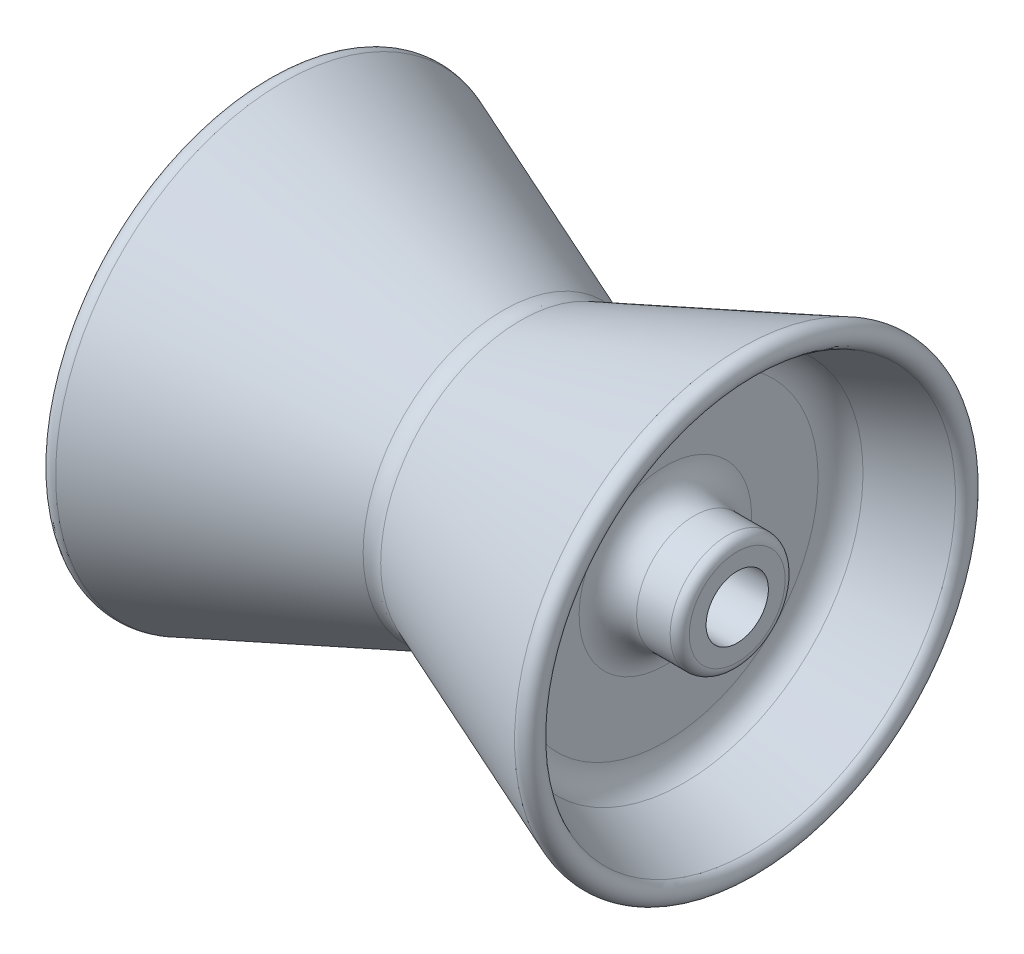
SolidWorks part; units mm, degrees
ref_plane "Front Plane" through (0, 0, 0) normal (0, 0, 1) x (1, 0, 0)
ref_plane "Top Plane" through (0, 0, 0) normal (0, 1, 0) x (1, 0, 0)
ref_plane "Right Plane" through (0, 0, 0) normal (1, 0, 0) x (0, 0, -1)
sketch "Sketch1" plane through (0, 0, 0) normal (0, 0, 1) x (1, 0, 0)
  line L0 (-0.0308, 0) -> (49999.9708, 0) construction
  line L1 (0, -0.0056) -> (0, 50000.0118) construction
  line L2 (-248.2263, 214.4399) -> (-179.0171, 187.2123)
  line L3 (-160, 90) -> (-160, 159.295)
  line L4 (-190, 60) -> (-225, 60)
  line L5 (-235, 50) -> (-235, 32.5)
  line L6 (-239.4399, 236.7737) -> (-9.1525, 146.1763)
  line L7 (-130, 121.0166) -> (-130, 32.5)
  line L8 (-130, 32.5) -> (-235, 32.5)
  line L9 (-90.9674, 149.6245) -> (-15.0544, 125.6558)
  line L12 (90.9674, 149.6245) -> (15.0544, 125.6558)
  line L13 (130, 32.5) -> (235, 32.5)
  line L14 (130, 121.0166) -> (130, 32.5)
  line L15 (239.4399, 236.7737) -> (9.1525, 146.1763)
  line L16 (235, 50) -> (235, 32.5)
  line L17 (190, 60) -> (225, 60)
  line L18 (160, 90) -> (160, 159.295)
  line L19 (248.2263, 214.4399) -> (179.0171, 187.2123)
  arc A0 (-160, 90) -> (-190, 60) centre (-190, 90) cw
  arc A2 (-248.2263, 214.4399) -> (-239.4399, 236.7737) centre (-243.8331, 225.6068) cw
  arc A3 (-130, 121.0166) -> (-90.9674, 149.6245) centre (-100, 121.0166) cw
  arc A4 (-179.0171, 187.2123) -> (-160, 159.295) centre (-190, 159.295) cw
  arc A6 (-225, 60) -> (-235, 50) centre (-225, 50) ccw
  arc A7 (225, 60) -> (235, 50) centre (225, 50) cw
  arc A9 (179.0171, 187.2123) -> (160, 159.295) centre (190, 159.295) ccw
  arc A10 (130, 121.0166) -> (90.9674, 149.6245) centre (100, 121.0166) ccw
  arc A11 (248.2263, 214.4399) -> (239.4399, 236.7737) centre (243.8331, 225.6068) ccw
  arc A13 (160, 90) -> (190, 60) centre (190, 90) ccw
  arc A14 (-15.0544, 125.6558) -> (15.0544, 125.6558) centre (0, 173.3356) ccw
  arc A15 (-9.1525, 146.1763) -> (9.1525, 146.1763) centre (0, 169.4407) ccw
  point P14 (0, 144.4407)
  point P23 (-213.6217, 200.8261)
  point P26 (0, 123.3356)
  point P28 (-124.2962, 191.475)
  point P29 (-53.0109, 137.6401)
  point P30 (-130, 76.7583)
  point P31 (-255, 230)
  point P43 (-168.7868, 68.7868)
  point P54 (-235, 41.25)
  point P55 (-160, 124.6475)
  point P56 (-207.5, 60)
  dimension "D2" = 50
  dimension "D3" = 20
  dimension "D1" = 12
  dimension "D4" = 230
  dimension "D5" = 75
  dimension "D6" = 30
  dimension "D12" = 30
  dimension "D8" = 25
  dimension "D14" = 10
  dimension "D18" = 30
  dimension "D19" = 30
  dimension "D20" = 30
  dimension "D7" = 160
  dimension "D9" = 24
  dimension "D10" = 24
  dimension "D11" = 60
  dimension "D13" = 130
  dimension "D15" = 144.4407
  dimension "D16" = 32.5
  dimension "D17" = 68.7868
  dimension "D21" = 123.3356
revolve "Revolve2" add sketch "Sketch1" angle 360 about L0
